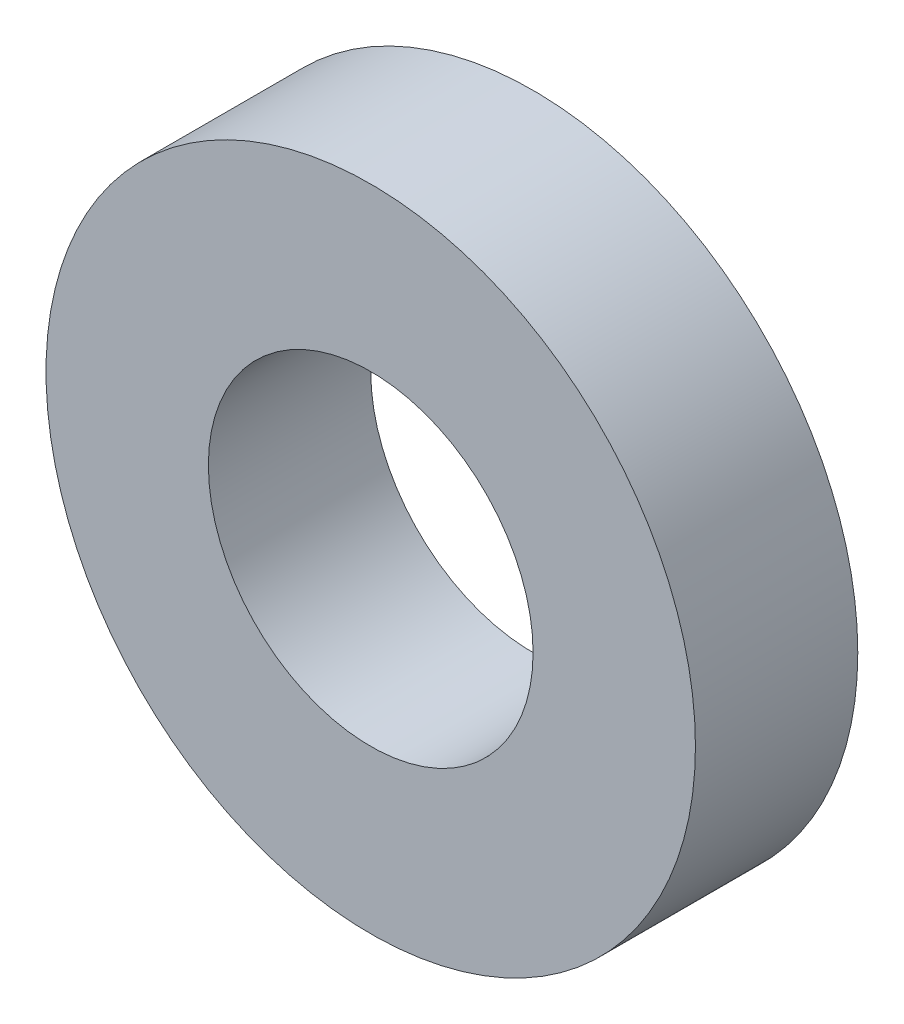
SolidWorks part; units mm, degrees
ref_plane "Front Plane" through (0, 0, 0) normal (0, 0, 1) x (1, 0, 0)
ref_plane "Top Plane" through (0, 0, 0) normal (0, 1, 0) x (1, 0, 0)
ref_plane "Right Plane" through (0, 0, 0) normal (1, 0, 0) x (0, 0, -1)
sketch "Sketch1" plane through (0, 0, 0) normal (0, 0, 1) x (1, 0, 0)
  circle A0 centre (0, 0) radius 6.35
  circle A1 centre (0, 0) radius 3.175
  dimension "D1" = 12.7
  dimension "D2" = 6.35
extrude "Boss-Extrude1" add sketch "Sketch1" along normal blind 3.175
